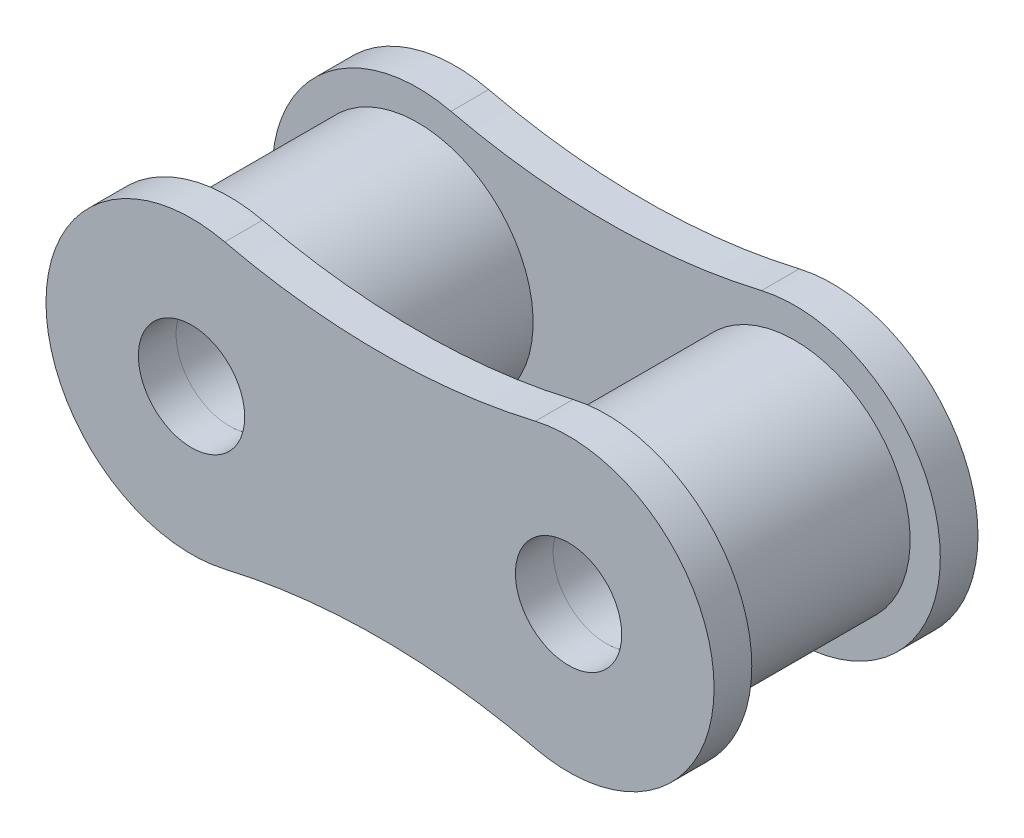
SolidWorks part; units mm, degrees
ref_plane "Front Plane" through (0, 0, 0) normal (0, 0, 1) x (1, 0, 0)
ref_plane "Top Plane" through (0, 0, 0) normal (0, 1, 0) x (1, 0, 0)
ref_plane "Right Plane" through (0, 0, 0) normal (1, 0, 0) x (0, 0, -1)
sketch "Sketch1" plane through (0, 0, 0) normal (0, 0, 1) x (1, 0, 0)
  line L0 (-6.35, 0) -> (6.35, 0) construction
  line L1 (-6.35, 4.9022) -> (-6.35, -4.9022) construction
  line L2 (0, -4.1669) -> (0, 4.1669) construction
  line L3 (6.35, -4.9022) -> (6.35, 4.9022) construction
  circle A0 centre (-6.35, 0) radius 3.8862
  circle A1 centre (6.35, 0) radius 3.8862
  circle A2 centre (-6.35, 0) radius 1.7907
  circle A3 centre (6.35, 0) radius 1.7907
  arc A4 (-5.2297, 4.7725) -> (-5.2297, -4.7725) centre (-6.35, 0) ccw
  arc A5 (5.2297, -4.7725) -> (5.2297, 4.7725) centre (6.35, 0) ccw
  arc A6 (-5.2297, 4.7725) -> (5.2297, 4.7725) centre (0, 27.0503) ccw
  arc A7 (-5.2297, -4.7725) -> (5.2297, -4.7725) centre (0, -27.0503) cw
  dimension "Roller Dia" = 7.7724
  dimension "Pin Dia" = 3.5814
  dimension "Pitch" = 12.7
  dimension "H" = 9.8044
  dimension "D2" = 8.3337
sketch "Sketch2" plane through (0, 0, 0) normal (0, 1, 0) x (1, 0, 0)
  line L0 (0, 3.175) -> (0, -3.175) construction
  point P2 (0, -4.445)
  point P4 (0, 4.445)
  point P5 (0, 4.4958)
  point P6 (0, 5.7658)
  dimension "W" = 6.35
  dimension "T" = 1.27
  dimension "D1" = 1.27
  dimension "D2" = 1.27
  dimension "D3" = 0.0508
ref_plane "Plane1" through (0, 0, 3.175) normal (0, 0, 1) x (1, 0, 0)
ref_plane "Plane2" through (0, 0, -4.4958) normal (0, 0, 1) x (1, 0, 0)
sketch "Sketch4" plane through (0, 0, 0) normal (0, 0, 1) x (1, 0, 0)
  circle A0 centre (-6.35, 0) radius 3.8862 construction
  circle A1 centre (-6.35, 0) radius 3.8862
  circle A2 centre (6.35, 0) radius 3.8862 construction
  circle A3 centre (6.35, 0) radius 3.8862
  circle A4 centre (-6.35, 0) radius 1.8161
  circle A5 centre (6.35, 0) radius 1.8161
  dimension "D1" = 3.6322
  dimension "D2" = 3.6322
extrude "Boss-Extrude1" add sketch "Sketch4" along normal mid plane 6.35
sketch "Sketch5" plane through (0, 0, 3.175) normal (0, 0, 1) x (1, 0, 0)
  arc A0 (-5.2297, 4.7725) -> (-5.2297, -4.7725) centre (-6.35, 0) ccw construction
  arc A1 (-5.2297, 4.7725) -> (5.2297, 4.7725) centre (0, 27.0503) ccw construction
  circle A2 centre (-6.35, 0) radius 1.7907 construction
  arc A3 (5.2297, -4.7725) -> (5.2297, 4.7725) centre (6.35, 0) ccw construction
  circle A4 centre (6.35, 0) radius 1.7907 construction
  arc A5 (5.2297, -4.7725) -> (-5.2297, -4.7725) centre (0, -27.0503) ccw construction
  arc A6 (-5.2297, 4.7725) -> (-5.2297, -4.7725) centre (-6.35, 0) ccw
  arc A7 (-5.2297, 4.7725) -> (5.2297, 4.7725) centre (0, 27.0503) ccw
  circle A8 centre (-6.35, 0) radius 1.7907
  arc A9 (5.2297, -4.7725) -> (5.2297, 4.7725) centre (6.35, 0) ccw
  circle A10 centre (6.35, 0) radius 1.7907
  arc A11 (5.2297, -4.7725) -> (-5.2297, -4.7725) centre (0, -27.0503) ccw
extrude "Boss-Extrude2" add sketch "Sketch5" along normal up to vertex (1.27 mm away) separate body up to point (0, 0, 4.445)
mirror "Mirror3" about plane through (0, 0, 0) normal (0, 0, 1) of bodies 103
combine bodies "Combine2" operation type add bodies to combine 120 103 102 101
equation "\"D2@Sketch1\" =\"H@Sketch1\"*.85"
equation "\"D1@Sketch2\" = \"T@Sketch2\""
equation "\"D1@Sketch4\" = \"Pin Dia@Sketch1\"+.002"
equation "\"D2@Sketch4\" = \"D1@Sketch4\""
equation "\"D1@Boss-Extrude1\" = \"W@Sketch2\""
equation "\"D2@Sketch2\" = \"T@Sketch2\""
